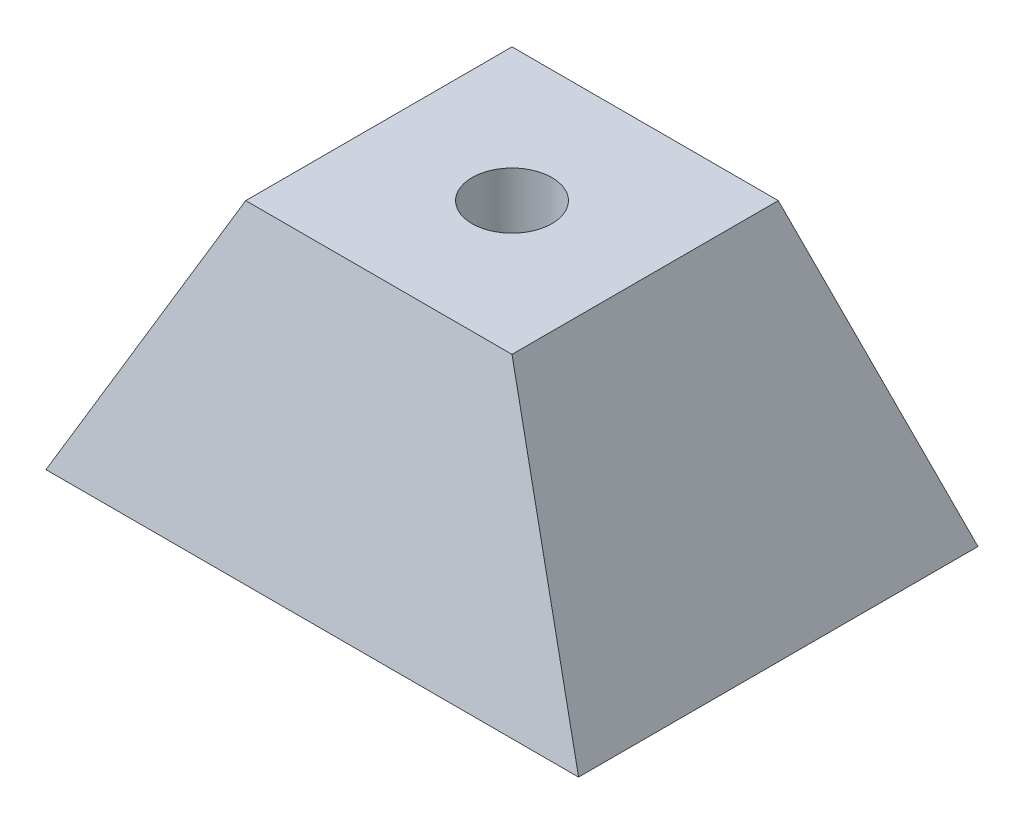
SolidWorks part; units mm, degrees
material "Plain Carbon Steel"
ref_plane "Front Plane" through (0, 0, 0) normal (0, 0, 1) x (1, 0, 0)
ref_plane "Top Plane" through (0, 0, 0) normal (0, 1, 0) x (1, 0, 0)
ref_plane "Right Plane" through (0, 0, 0) normal (1, 0, 0) x (0, 0, -1)
ref_plane "Plane1" through (0, 12.7, 0) normal (0, 1, 0) x (1, 0, 0)
sketch "Sketch1" plane through (0, 0, 0) normal (0, 1, 0) x (1, 0, 0)
  line L1 (-12.7, -9.525) -> (12.7, -9.525)
  line L2 (-12.7, -9.525) -> (-12.7, 9.525)
  line L3 (-12.7, 9.525) -> (12.7, 9.525)
  line L4 (12.7, -9.525) -> (12.7, 9.525)
  line L5 (-12.7, -9.525) -> (12.7, 9.525) construction
  line L6 (-12.7, 9.525) -> (12.7, -9.525) construction
  point P0 (0, 0)
  point P6 (0, 0)
  point P11 (0, 0)
  point P12 (-9.5951, -19.7926)
  dimension "D1" = 25.4
  dimension "D2" = 19.05
sketch "Sketch2" plane through (0, 12.7, 0) normal (0, 1, 0) x (1, 0, 0)
  line L1 (-6.35, -6.35) -> (6.35, -6.35)
  line L2 (-6.35, -6.35) -> (-6.35, 6.35)
  line L3 (-6.35, 6.35) -> (6.35, 6.35)
  line L4 (6.35, -6.35) -> (6.35, 6.35)
  line L5 (-6.35, -6.35) -> (6.35, 6.35) construction
  line L6 (-6.35, 6.35) -> (6.35, -6.35) construction
  point P0 (0, 0)
  dimension "D1" = 12.7
  dimension "D2" = 12.7
loft "Loft1" add profiles "Sketch2", "Sketch1"
sketch "Sketch3" plane through (0, 12.7, 0) normal (0, 1, 0) x (1, 0, 0)
  circle A0 centre (0, 0) radius 1.905
  dimension "D1" = 3.81
extrude "Cut-Extrude1" cut sketch "Sketch3" against normal through all
